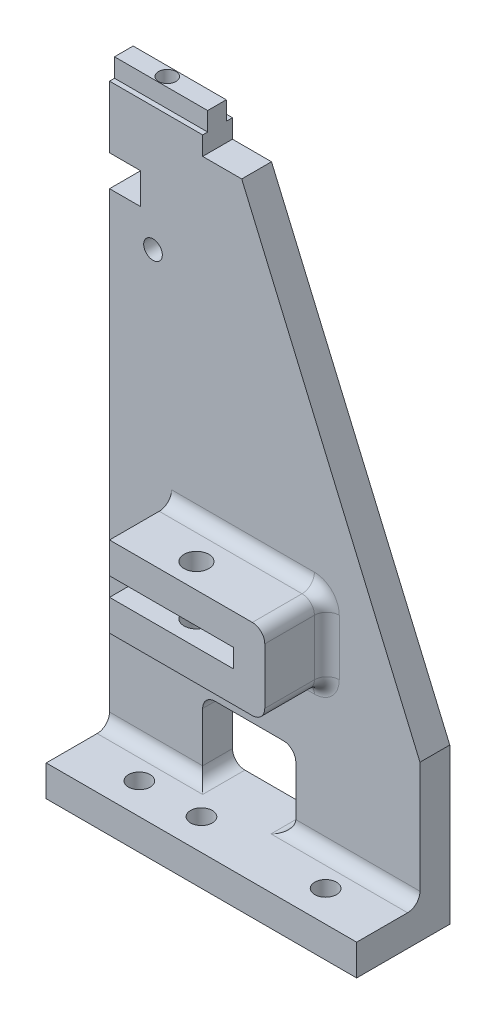
SolidWorks part; units mm, degrees
ref_plane "前视基准面" through (0, 0, 0) normal (0, 0, 1) x (1, 0, 0)
ref_plane "上视基准面" through (0, 0, 0) normal (0, 1, 0) x (1, 0, 0)
ref_plane "右视基准面" through (0, 0, 0) normal (1, 0, 0) x (0, 0, -1)
sketch "草图1" plane through (0, 0, 0) normal (0, 0, 1) x (1, 0, 0)
  line L0 (-23.338, 53.1861) -> (-23.338, 63.1861)
  line L1 (-23.338, -26.8139) -> (-8.338, -26.8139)
  line L2 (26.662, -26.8139) -> (26.662, -6.8139)
  line L3 (-23.338, 53.1861) -> (-18.338, 53.1861)
  line L4 (-23.338, -6.8139) -> (-23.338, -26.8139)
  line L5 (-23.338, -6.8139) -> (-23.338, 48.1861)
  line L6 (-23.338, 63.1861) -> (-3.338, 63.1861)
  line L7 (-3.338, 63.1861) -> (26.662, -6.8139)
  line L8 (6.662, -26.8139) -> (26.662, -26.8139)
  line L9 (-23.338, 48.1861) -> (-18.338, 48.1861)
  line L10 (-18.338, 53.1861) -> (-18.338, 48.1861)
  line L12 (-8.338, -26.8139) -> (-8.338, -14.8139)
  line L13 (-8.338, -14.8139) -> (6.662, -14.8139)
  line L14 (6.662, -26.8139) -> (6.662, -14.8139)
  circle A0 centre (-16.338, 43.1861) radius 1.5
  point P16 (-8.338, -20.8139)
  dimension "D8" = 3
  dimension "D1" = 50
  dimension "D2" = 20
  dimension "D3" = 20
  dimension "D4" = 90
  dimension "D5" = 5
  dimension "D6" = 5
  dimension "D7" = 10
  dimension "D9" = 20
  dimension "D10" = 7
  dimension "D11" = 15
  dimension "D12" = 12
  dimension "D13" = 20
extrude "凸台-拉伸1" add sketch "草图1" along normal blind 4.8
sketch "草图2" plane through (0, -26.8139, 0) normal (0, -1, 0) x (1, 0, 0)
  line L0 (26.662, 4.8) -> (26.662, 0) construction
  line L1 (-23.338, 0) -> (26.662, 0)
  line L2 (-23.338, 0) -> (-23.338, 15)
  line L3 (-23.338, 15) -> (26.662, 15)
  line L4 (26.662, 0) -> (26.662, 15)
  circle A0 centre (-13.338, 10) radius 1.75
  circle A1 centre (16.662, 10) radius 1.75
  circle A2 centre (-3.338, 10) radius 1.75
  dimension "D2" = 3.5
  dimension "D3" = 3.5
  dimension "D4" = 3.5
  dimension "D1" = 15
  dimension "D5" = 5
  dimension "D6" = 5
  dimension "D7" = 5
  dimension "D8" = 10
  dimension "D9" = 10
  dimension "D10" = 0
  dimension "D11" = 30
extrude "凸台-拉伸2" add sketch "草图2" along normal blind 5
sketch "草图4" plane through (0, 0, 4.8) normal (0, 0, 1) x (1, 0, 0)
  line L0 (11.662, 9.1861) -> (11.662, -3.8139)
  line L1 (-13.338, 9.1861) -> (11.662, 9.1861)
  line L2 (-13.338, 9.1861) -> (-13.338, 4.1861)
  line L3 (26.662, -31.8139) -> (-23.338, -31.8139) construction
  line L4 (26.662, -26.8139) -> (26.662, -6.8139) construction
  line L5 (6.662, 4.1861) -> (-3.338, 4.1861)
  line L7 (11.662, -3.8139) -> (-13.338, -3.8139)
  line L8 (-13.338, -3.8139) -> (-13.338, 1.1861)
  line L9 (-13.338, 1.1861) -> (6.662, 1.1861)
  line L10 (6.662, 4.1861) -> (6.662, 1.1861)
  line L12 (-3.338, 4.1861) -> (-13.338, 4.1861)
  point P10 (26.662, -16.8139)
  dimension "D1" = 5
  dimension "D2" = 3
  dimension "D3" = 13
  dimension "D4" = 25
  dimension "D5" = 5
  dimension "D6" = 28
  dimension "D7" = 15
extrude "凸台-拉伸3" add sketch "草图4" along normal blind 10
sketch "草图5" plane through (0, 9.1861, 0) normal (0, 1, 0) x (1, 0, 0)
  line L1 (11.662, -14.8) -> (-13.338, -14.8) construction
  line L2 (11.662, -14.8) -> (11.662, -4.8) construction
  circle A0 centre (-3.338, -10.8) radius 2
  dimension "D3" = 4
  dimension "D1" = 15
  dimension "D2" = 4
extrude "切除-拉伸1" cut sketch "草图5" against normal blind 20
fillet "圆角1" radius 2 2 edges at (11.662, -3.8139, 9.8) (11.662, 9.1861, 9.8)
fillet "圆角2" radius 2 5 edges at (-1.838, 9.1861, 4.8) (-1.838, -3.8139, 4.8) (11.0762, -3.2282, 4.8) (11.662, 2.6861, 4.8) (11.0762, 8.6003, 4.8)
fillet "圆角3" radius 2 6 edges at (-15.838, -26.8139, 4.8) (16.662, -26.8139, 4.8) (-8.338, -26.8139, 2.4) (6.662, -26.8139, 2.4) (-8.338, -14.8139, 2.4) (6.662, -14.8139, 2.4)
sketch "草图6" plane through (0, 63.1861, 0) normal (0, 1, 0) x (1, 0, 0)
  line L0 (-23.338, -4.8) -> (-23.338, 0) construction
  line L1 (-23.338, -1) -> (-8.338, -1)
  line L2 (-23.338, -1) -> (-23.338, -4)
  line L3 (-23.338, -4) -> (-8.338, -4)
  line L4 (-8.338, -1) -> (-8.338, -4)
  line L5 (-3.338, 0) -> (-23.338, 0) construction
  dimension "D1" = 15
  dimension "D2" = 3
  dimension "D3" = 1
extrude "凸台-拉伸5" add sketch "草图6" along normal blind 3
sketch "草图7" plane through (0, 66.1861, 0) normal (0, 1, 0) x (1, 0, 0)
  line L0 (-8.338, -1) -> (-23.338, -1) construction
  line L1 (-23.338, -1) -> (-23.338, -4) construction
  circle A0 centre (-16.338, -2.5) radius 1.4
  point P6 (-23.338, -2.5)
  dimension "D1" = 2.8
  dimension "D2" = 1.5
  dimension "D3" = 7
extrude "切除-拉伸2" cut sketch "草图7" against normal blind 5
sketch "草图8" plane through (0, 0, 4.8) normal (0, 0, 1) x (1, 0, 0)
  line L0 (-8.338, 63.1861) -> (-8.338, 60.1861)
  line L1 (-8.338, 60.1861) -> (-2.0523, 60.1861)
  line L2 (26.662, -6.8139) -> (-3.338, 63.1861) construction
  line L3 (-2.0523, 60.1861) -> (-3.338, 63.1861)
  line L4 (-3.338, 63.1861) -> (-8.338, 63.1861)
  dimension "D1" = 3
extrude "切除-拉伸3" cut sketch "草图8" against normal through all
